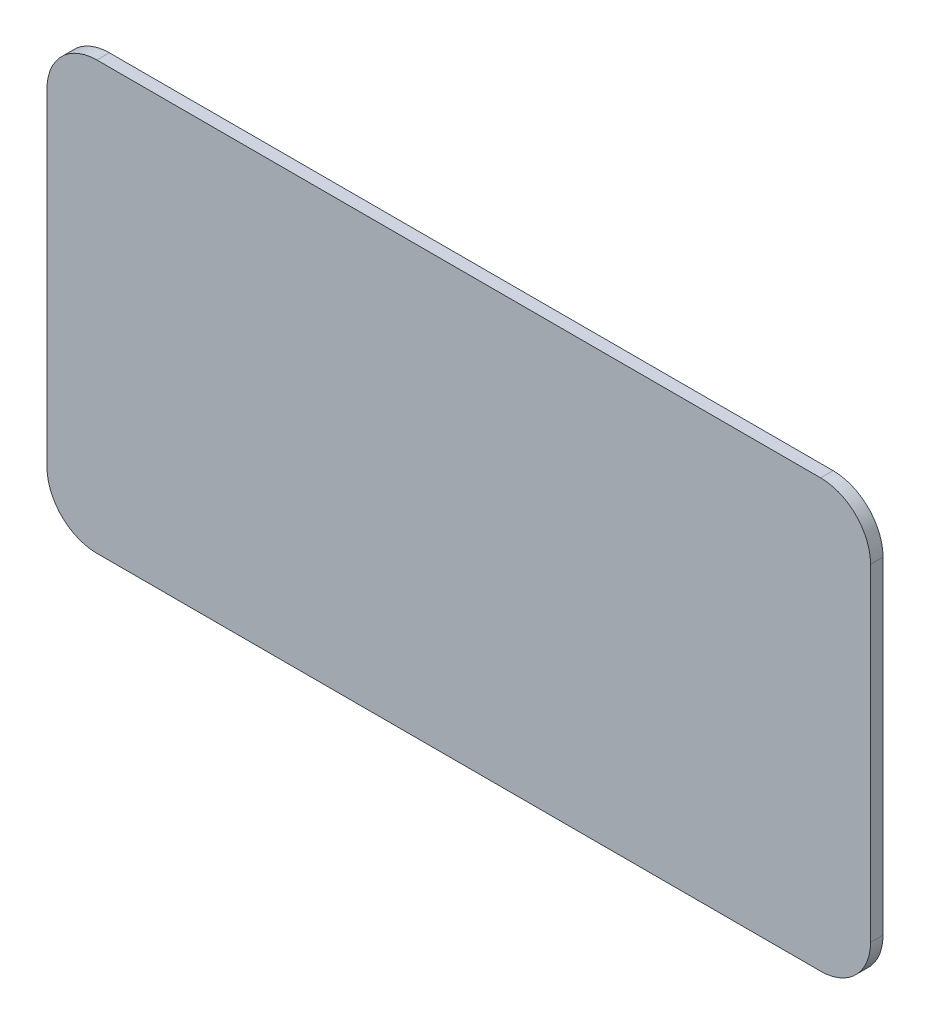
SolidWorks part; units mm, degrees
material "Acrylic (Medium-high impact)"
ref_plane "Front Plane" through (0, 0, 0) normal (0, 0, 1) x (1, 0, 0)
ref_plane "Top Plane" through (0, 0, 0) normal (0, 1, 0) x (1, 0, 0)
ref_plane "Right Plane" through (0, 0, 0) normal (1, 0, 0) x (0, 0, -1)
sketch "Sketch1" plane through (0, 0, 0) normal (0, 0, 1) x (1, 0, 0)
  line L1 (0, 0) -> (419.1, 0)
  line L2 (0, 0) -> (0, -217.424)
  line L3 (0, -217.424) -> (419.1, -217.424)
  line L4 (419.1, 0) -> (419.1, -217.424)
  dimension "D1" = 419.1
  dimension "D2" = 217.424
extrude "Boss-Extrude1" add sketch "Sketch1" along normal blind 6.35
fillet "Fillet1" radius 25.4 1 edges at (419.1, 0, 3.175)
fillet "Fillet2" radius 25.4 1 edges at (0, 0, 3.175)
fillet "Fillet3" radius 25.4 1 edges at (0, -217.424, 3.175)
fillet "Fillet4" radius 25.4 1 edges at (419.1, -217.424, 3.175)
